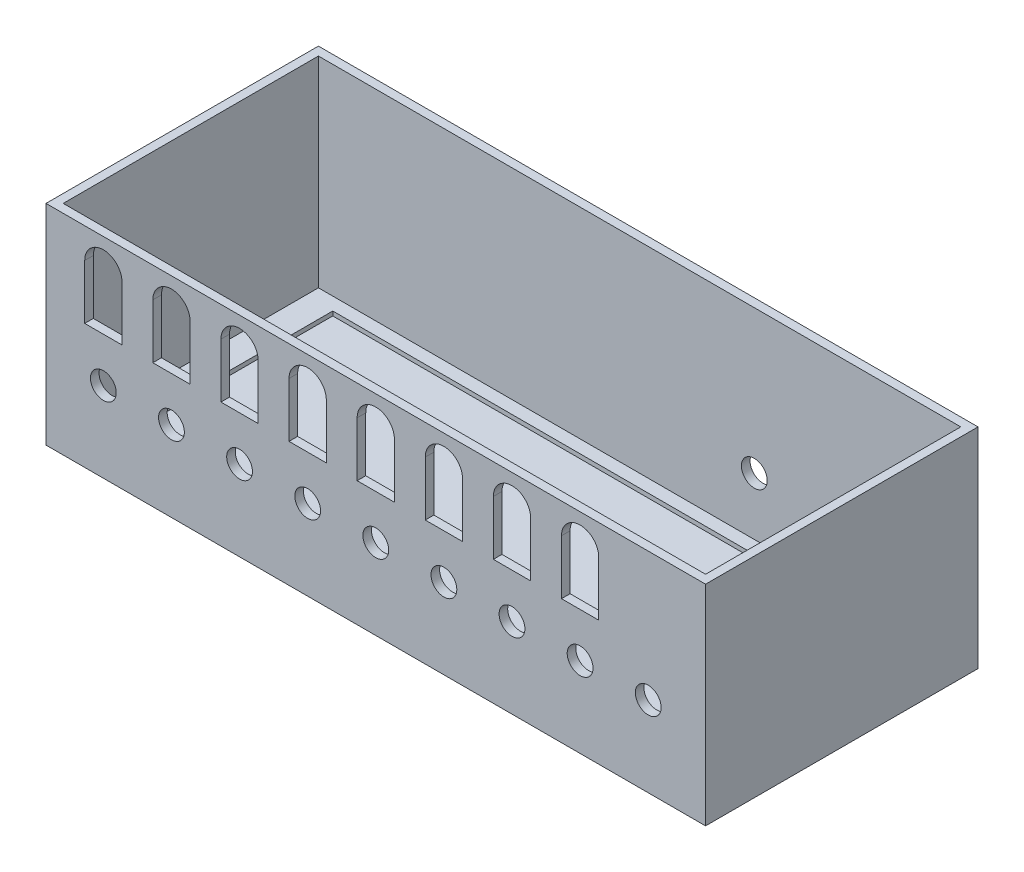
SolidWorks part; units mm, degrees
ref_plane "Front Plane" through (0, 0, 0) normal (0, 0, 1) x (1, 0, 0)
ref_plane "Top Plane" through (0, 0, 0) normal (0, 1, 0) x (1, 0, 0)
ref_plane "Right Plane" through (0, 0, 0) normal (1, 0, 0) x (0, 0, -1)
sketch "Sketch1" plane through (0, 0, 0) normal (0, 1, 0) x (1, 0, 0)
  line L1 (-115, -47.5) -> (115, -47.5)
  line L2 (-115, -47.5) -> (-115, 47.5)
  line L3 (-115, 47.5) -> (115, 47.5)
  line L4 (115, -47.5) -> (115, 47.5)
  line L5 (-115, -47.5) -> (115, 47.5) construction
  line L6 (-115, 47.5) -> (115, -47.5) construction
  point P0 (0, 0)
  dimension "D1" = 230
  dimension "D2" = 95
extrude "Boss-Extrude1" add sketch "Sketch1" along normal blind 3
sketch "Sketch2" plane through (0, 3, 0) normal (0, 1, 0) x (1, 0, 0)
  line L1 (-102.5, -40) -> (102.5, -40)
  line L2 (-102.5, -40) -> (-102.5, 40)
  line L3 (-102.5, 40) -> (102.5, 40)
  line L4 (102.5, -40) -> (102.5, 40)
  line L5 (-102.5, -40) -> (102.5, 40) construction
  line L6 (-102.5, 40) -> (102.5, -40) construction
  point P0 (0, 0)
  dimension "D1" = 80
  dimension "D2" = 205
extrude "Cut-Extrude1" cut sketch "Sketch2" against normal blind 1.5
sketch "Sketch3" plane through (0, 3, 0) normal (0, 1, 0) x (1, 0, 0)
  line L1 (-115, -47.5) -> (115, -47.5)
  line L2 (-115, -47.5) -> (-115, 47.5)
  line L3 (-115, 47.5) -> (115, 47.5)
  line L4 (115, -47.5) -> (115, 47.5)
  line L5 (-115, -47.5) -> (115, 47.5) construction
  line L6 (-115, 47.5) -> (115, -47.5) construction
  line L7 (-112, -44.5) -> (112, -44.5)
  line L8 (-112, -44.5) -> (-112, 44.5)
  line L9 (-112, 44.5) -> (112, 44.5)
  line L10 (112, -44.5) -> (112, 44.5)
  line L11 (-112, -44.5) -> (112, 44.5) construction
  line L12 (-112, 44.5) -> (112, -44.5) construction
  point P0 (0, 0)
  point P7 (0, 0)
  dimension "D1" = 224
  dimension "D2" = 89
extrude "Boss-Extrude2" add sketch "Sketch3" along normal blind 70
sketch "Sketch4" plane through (0, 0, 47.5) normal (0, 0, 1) x (1, 0, 0)
  line L0 (0, 0) -> (0, 3) construction
  line L1 (-115, 0) -> (115, 0) construction
  line L2 (0, 3) -> (23.75, 3) construction
  line L3 (23.75, 3) -> (47.5, 3) construction
  line L4 (47.5, 3) -> (71.25, 3) construction
  line L5 (71.25, 3) -> (95, 3) construction
  line L6 (0, 3) -> (-23.75, 3) construction
  line L7 (-23.75, 3) -> (-47.5, 3) construction
  line L8 (-47.5, 3) -> (-71.25, 3) construction
  line L9 (-71.25, 3) -> (-95, 3) construction
  line L10 (-95, 3) -> (-115, 3) construction
  line L11 (-115, 73) -> (-115, 0) construction
  line L12 (95, 3) -> (115, 3) construction
  line L13 (115, 73) -> (115, 0) construction
  line L14 (95, 3) -> (95, 28) construction
  line L15 (71.25, 3) -> (71.25, 28) construction
  line L16 (47.5, 3) -> (47.5, 28) construction
  line L17 (23.75, 3) -> (23.75, 28) construction
  line L18 (0, 3) -> (0, 28) construction
  line L19 (-23.75, 3) -> (-23.75, 28) construction
  line L20 (-47.5, 3) -> (-47.5, 28) construction
  line L21 (-71.25, 3) -> (-71.25, 28) construction
  line L22 (-95, 3) -> (-95, 28) construction
  line L23 (-95, 28) -> (-95, 53) construction
  line L24 (-71.25, 28) -> (-71.25, 53) construction
  line L25 (-47.5, 28) -> (-47.5, 53) construction
  line L26 (-23.75, 28) -> (-23.75, 53) construction
  line L27 (0, 28) -> (0, 53) construction
  line L28 (23.75, 28) -> (23.75, 53) construction
  line L29 (47.5, 28) -> (47.5, 53) construction
  line L30 (71.25, 28) -> (71.25, 53) construction
  line L31 (-101.5, 62.5) -> (-88.5, 62.5) construction
  line L33 (-101.5, 62.5) -> (-101.5, 43.5)
  line L34 (-101.5, 43.5) -> (-88.5, 43.5)
  line L35 (-88.5, 62.5) -> (-88.5, 43.5)
  line L36 (-101.5, 62.5) -> (-88.5, 43.5) construction
  line L37 (-101.5, 43.5) -> (-88.5, 62.5) construction
  line L39 (-77.75, 62.5) -> (-77.75, 43.5)
  line L40 (-77.75, 43.5) -> (-64.75, 43.5)
  line L41 (-64.75, 62.5) -> (-64.75, 43.5)
  line L42 (-77.75, 62.5) -> (-64.75, 43.5) construction
  line L43 (-77.75, 43.5) -> (-64.75, 62.5) construction
  line L45 (-54, 62.5) -> (-54, 43.5)
  line L46 (-54, 43.5) -> (-41, 43.5)
  line L47 (-41, 62.5) -> (-41, 43.5)
  line L48 (-54, 62.5) -> (-41, 43.5) construction
  line L49 (-54, 43.5) -> (-41, 62.5) construction
  line L51 (-30.25, 62.5) -> (-30.25, 43.5)
  line L52 (-30.25, 43.5) -> (-17.25, 43.5)
  line L53 (-17.25, 62.5) -> (-17.25, 43.5)
  line L54 (-30.25, 62.5) -> (-17.25, 43.5) construction
  line L55 (-30.25, 43.5) -> (-17.25, 62.5) construction
  line L57 (-6.5, 62.5) -> (-6.5, 43.5)
  line L58 (-6.5, 43.5) -> (6.5, 43.5)
  line L59 (6.5, 62.5) -> (6.5, 43.5)
  line L60 (-6.5, 62.5) -> (6.5, 43.5) construction
  line L61 (-6.5, 43.5) -> (6.5, 62.5) construction
  line L63 (17.25, 62.5) -> (17.25, 43.5)
  line L64 (17.25, 43.5) -> (30.25, 43.5)
  line L65 (30.25, 62.5) -> (30.25, 43.5)
  line L66 (17.25, 62.5) -> (30.25, 43.5) construction
  line L67 (17.25, 43.5) -> (30.25, 62.5) construction
  line L69 (41, 62.5) -> (41, 43.5)
  line L70 (41, 43.5) -> (54, 43.5)
  line L71 (54, 62.5) -> (54, 43.5)
  line L72 (41, 62.5) -> (54, 43.5) construction
  line L73 (41, 43.5) -> (54, 62.5) construction
  line L75 (64.75, 62.5) -> (64.75, 43.5)
  line L76 (64.75, 43.5) -> (77.75, 43.5)
  line L77 (77.75, 62.5) -> (77.75, 43.5)
  line L78 (64.75, 62.5) -> (77.75, 43.5) construction
  line L79 (64.75, 43.5) -> (77.75, 62.5) construction
  line L80 (-64.75, 62.5) -> (-77.75, 62.5) construction
  line L81 (-54, 62.5) -> (-41, 62.5) construction
  line L82 (-30.25, 62.5) -> (-17.25, 62.5) construction
  line L83 (-6.5, 62.5) -> (6.5, 62.5) construction
  line L84 (17.25, 62.5) -> (30.25, 62.5) construction
  line L85 (41, 62.5) -> (54, 62.5) construction
  line L86 (64.75, 62.5) -> (77.75, 62.5) construction
  circle A0 centre (95, 28) radius 4.5
  circle A1 centre (71.25, 28) radius 4.5
  circle A2 centre (47.5, 28) radius 4.5
  circle A3 centre (23.75, 28) radius 4.5
  circle A4 centre (0, 28) radius 4.5
  circle A5 centre (-23.75, 28) radius 4.5
  circle A6 centre (-47.5, 28) radius 4.5
  circle A7 centre (-71.25, 28) radius 4.5
  circle A8 centre (-95, 28) radius 4.5
  arc A9 (-101.5, 62.5) -> (-88.5, 62.5) centre (-95, 62.5) cw
  arc A10 (-77.75, 62.5) -> (-64.75, 62.5) centre (-71.25, 62.5) cw
  arc A11 (-54, 62.5) -> (-41, 62.5) centre (-47.5, 62.5) cw
  arc A12 (-30.25, 62.5) -> (-17.25, 62.5) centre (-23.75, 62.5) cw
  arc A13 (-6.5, 62.5) -> (6.5, 62.5) centre (0, 62.5) cw
  arc A14 (17.25, 62.5) -> (30.25, 62.5) centre (23.75, 62.5) cw
  arc A15 (41, 62.5) -> (54, 62.5) centre (47.5, 62.5) cw
  arc A16 (64.75, 62.5) -> (77.75, 62.5) centre (71.25, 62.5) cw
  dimension "D4" = 9
  dimension "D8" = 6.5
  dimension "D1" = 3
  dimension "D2" = 20
  dimension "D3" = 25
  dimension "D5" = 25
  dimension "D6" = 13
  dimension "D7" = 19
extrude "Cut-Extrude2" cut sketch "Sketch4" against normal blind 3
sketch "Sketch5" plane through (0, 0, -47.5) normal (0, 0, -1) x (-1, 0, 0)
  line L0 (0, 0) -> (0, 23) construction
  line L1 (0, 23) -> (-40, 23) construction
  line L2 (-40, 23) -> (-70, 23) construction
  line L3 (-70, 23) -> (-100, 23) construction
  circle A0 centre (-100, 23) radius 4.5
  circle A1 centre (-70, 23) radius 4.5
  circle A2 centre (-40, 23) radius 4.5
  dimension "D4" = 9
  dimension "D1" = 23
  dimension "D2" = 30
  dimension "D3" = 40
extrude "Cut-Extrude3" cut sketch "Sketch5" against normal blind 3
